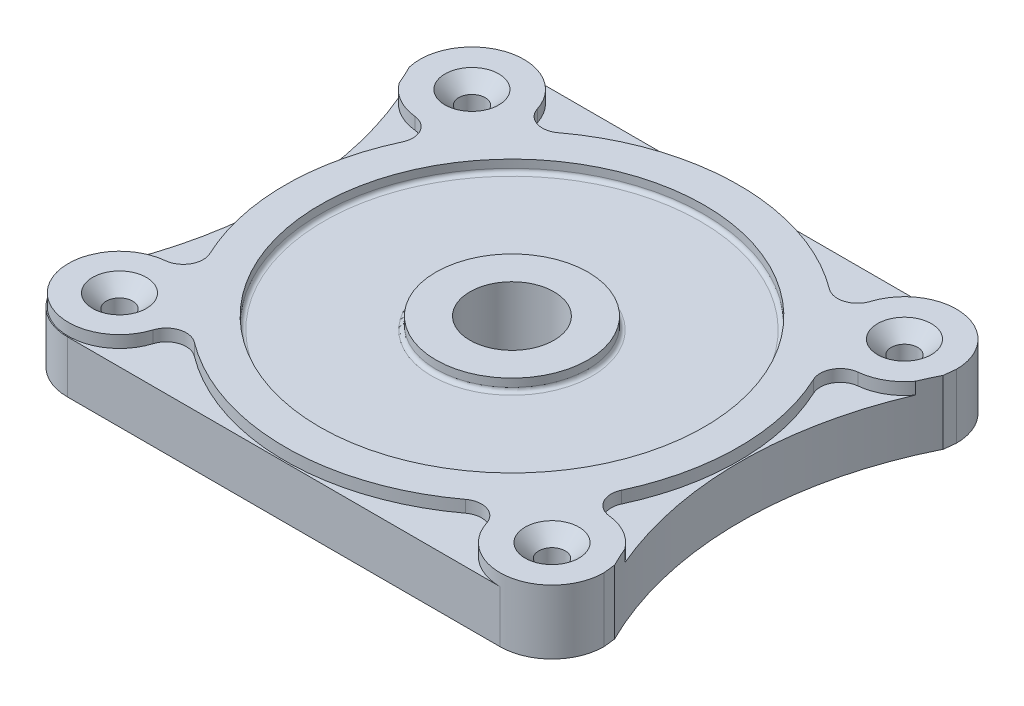
SolidWorks part; units mm, degrees
ref_plane "Front Plane" through (0, 0, 0) normal (0, 0, 1) x (1, 0, 0)
ref_plane "Top Plane" through (0, 0, 0) normal (0, 1, 0) x (1, 0, 0)
ref_plane "Right Plane" through (0, 0, 0) normal (1, 0, 0) x (0, 0, -1)
sketch "Sketch1" plane through (0, 0, 0) normal (0, 1, 0) x (1, 0, 0)
  line L1 (-67, 57) -> (67, 57)
  line L2 (-67, 57) -> (-67, -57)
  line L3 (-67, -57) -> (67, -57)
  line L4 (67, 57) -> (67, -57)
  line L5 (-67, 57) -> (67, -57) construction
  line L6 (-67, -57) -> (67, 57) construction
  point P1 (0, 0)
  dimension "D1" = 114
  dimension "D2" = 134
extrude "Boss-Extrude1" add sketch "Sketch1" along normal blind 16
sketch "Sketch2" plane through (0, 16, 0) normal (0, 1, 0) x (1, 0, 0)
  circle A0 centre (0, 0) radius 10.5
  dimension "D1" = 21
extrude "Cut-Extrude1" cut sketch "Sketch2" against normal through all
sketch "Sketch3" plane through (0, 16, 0) normal (0, 1, 0) x (1, 0, 0)
  circle A0 centre (0, 0) radius 19
  circle A1 centre (0, 0) radius 48
  dimension "D1" = 38
  dimension "D2" = 96
extrude "Cut-Extrude2" cut sketch "Sketch3" against normal blind 3
sketch "Sketch5" plane through (0, 0, 0) normal (0, -1, 0) x (1, 0, 0)
  circle A0 centre (0, 0) radius 19
  circle A1 centre (0, 0) radius 48
  dimension "D1" = 38
  dimension "D2" = 96
extrude "Cut-Extrude3" cut sketch "Sketch5" against normal blind 3
sketch "Sketch6" plane through (0, 16, 0) normal (0, 1, 0) x (1, 0, 0)
  line L0 (-220.4751, 0) -> (293.7406, 0) construction
  circle A1 centre (0, 0) radius 57 construction
  dimension "D1" = 114
hole_wizard "CSK for M6 Hex Socket Countersunk Cap Screw1" positions "Sketch7" profile "Sketch9" countersink size "M6" standard "ISO" end condition through all
sketch "Sketch7" plane through (0, 16, 0) normal (0, 1, 0) x (1, 0, 0)
  line L0 (-67, 57) -> (-67, -57) construction
  line L1 (67, -57) -> (67, 57) construction
  line L2 (-220.4751, 0) -> (293.7406, 0) construction
  point P0 (-54, 44)
  point P2 (54, 44)
  point P4 (54, -44)
  point P6 (-54, -44)
  dimension "D1" = 108
  dimension "D2" = 108
  dimension "D3" = 13
  dimension "D4" = 13
  dimension "D5" = 13
  dimension "D6" = 13
  dimension "D7" = 88
  dimension "D8" = 88
  dimension "D9" = 44
sketch "Sketch9" plane through (-54, 16, -44) normal (1, 0, 0) x (0, 0, 1)
  line L0 (0, 0) -> (0, 16)
  line L1 (0, 16) -> (3.3, 16)
  line L2 (3.3, 16) -> (3.3, 3.42)
  line L3 (3.3, 3.42) -> (6.72, 0)
  line L5 (6.72, 0) -> (0, 0)
  line L6 (-3.3, 3.42) -> (-6.72, 0) construction
  line L11 (0, -6.35) -> (0, 107.95) construction
  dimension "Thru Hole Dia." = 6.6
  dimension "Thru Hole Depth" = 16
  dimension "Near C'Sink Dia." = 13.44
  dimension "Near C'Sink Angle" = 90
sketch "Sketch10" plane through (0, 16, 0) normal (0, 1, 0) x (1, 0, 0)
  line L0 (-220.4751, 0) -> (293.7406, 0) construction
  circle A0 centre (149, 0) radius 92
  circle A1 centre (-149, 0) radius 92
  circle A2 centre (0, 0) radius 57 construction
  dimension "D1" = 184
  dimension "D2" = 184
extrude "Cut-Extrude4" cut sketch "Sketch10" against normal through all
sketch "Sketch12" plane through (0, 16, 0) normal (0, 1, 0) x (1, 0, 0)
  line L0 (-67, -41.7133) -> (-67, -57)
  line L1 (-67, -57) -> (-54, -57)
  line L2 (67, -41.7133) -> (67, -57)
  line L3 (67, -57) -> (54, -57)
  line L4 (-67, 41.7133) -> (-67, 57)
  line L5 (-67, 57) -> (-54, 57)
  line L6 (54, 57) -> (67, 57)
  line L7 (67, 57) -> (67, 41.7133)
  arc A0 (-54, 57) -> (-67, 44) centre (-54, 44) ccw
  arc A1 (67, 44) -> (54, 57) centre (54, 44) ccw
  arc A2 (-67, -44) -> (-54, -57) centre (-54, -44) ccw
  arc A3 (54, -57) -> (67, -44) centre (54, -44) ccw
  line M4 (67, 57) -> (-67, 57)
  line M5 (-67, 57) -> (-67, 41.7133)
  line M8 (-67, -57) -> (67, -57)
  line M9 (67, -57) -> (67, -41.7133)
  dimension "D1" = 26
  dimension "D2" = 26
  dimension "D3" = 26
  dimension "D4" = 26
extrude "Cut-Extrude5" cut sketch "Sketch12" against normal through all contours A2 L0 M8 | A3 M8 M9 | A0 M4 M5 | A1 L7 M4
sketch "Sketch13" plane through (0, 16, 0) normal (0, 1, 0) x (1, 0, 0)
  arc A0 (-51.3311, 23.9802) -> (-51.2311, -24.1932) centre (0, 0) ccw
  arc A1 (-55.2589, -31.3039) -> (-41.8199, -47.7973) centre (-54, -44) ccw
  arc A2 (41.6077, -47.9281) -> (55.3442, -31.0697) centre (54, -44) ccw
  arc A3 (-41.6077, 47.9281) -> (-55.3442, 31.0697) centre (-54, 44) ccw
  arc A4 (55.3442, 31.0697) -> (41.6077, 47.9281) centre (54, 44) ccw
  arc A5 (-51.3311, 23.9802) -> (-55.3442, 31.0697) centre (-55.8612, 26.0965) ccw
  arc A6 (-41.6077, 47.9281) -> (-33.8538, 45.4297) centre (-36.8414, 49.439) ccw
  arc A7 (33.8538, 45.4297) -> (41.6077, 47.9281) centre (36.8414, 49.439) ccw
  arc A8 (55.3442, 31.0697) -> (51.3311, 23.9802) centre (55.8612, 26.0965) ccw
  arc A9 (33.8538, 45.4297) -> (-33.8538, 45.4297) centre (0, 0) ccw
  arc A10 (51.3311, -23.9802) -> (55.3442, -31.0697) centre (55.8612, -26.0965) ccw
  arc A11 (-55.2589, -31.3039) -> (-51.2311, -24.1932) centre (-55.7523, -26.3283) ccw
  arc A12 (-34.0422, -45.2887) -> (-41.8199, -47.7973) centre (-37.0465, -49.2855) ccw
  arc A13 (41.6077, -47.9281) -> (33.8538, -45.4297) centre (36.8414, -49.439) ccw
  arc A14 (-34.0422, -45.2887) -> (33.8538, -45.4297) centre (0, 0) ccw
  arc A15 (51.3311, -23.9802) -> (51.3311, 23.9802) centre (0, 0) ccw
  dimension "D1" = 26
  dimension "D2" = 26
  dimension "D3" = 26
  dimension "D4" = 10
  dimension "D5" = 10
  dimension "D6" = 10
  dimension "D7" = 10
  dimension "D8" = 10
  dimension "D9" = 10
  dimension "D10" = 10
  dimension "D11" = 10
extrude "Cut-Extrude6" cut sketch "Sketch13" against normal blind 3 flip side to cut
sketch "Sketch14" plane through (0, 16, 0) normal (0, 1, 0) x (1, 0, 0)
  line L0 (67, 44) -> (66.6564, 41.0308)
  line L1 (66.6564, 41.0308) -> (67, 41.7133)
  line L2 (67, 41.7133) -> (67, 44)
  arc A0 (67, 41.7133) -> (66.6564, 41.0308) centre (149, 0) ccw construction
extrude "Cut-Extrude7" cut sketch "Sketch14" against normal through all
sketch "Sketch15" plane through (0, 13, 0) normal (0, 1, 0) x (1, 0, 0)
  line L0 (67, -41.7133) -> (66.6564, -41.0308)
  line L1 (67, -44) -> (67, -41.7133)
  line L2 (66.6564, -41.0308) -> (67, -44)
  arc A0 (41.6077, -47.9281) -> (66.6564, -41.0308) centre (54, -44) ccw construction
  arc A1 (67, -44) -> (66.6564, -41.0308) centre (54, -44) ccw construction
extrude "Cut-Extrude9" cut sketch "Sketch15" against normal through all
sketch "Sketch16" plane through (0, 16, 0) normal (0, 1, 0) x (1, 0, 0)
  line L0 (66.6564, -41.0308) -> (67, -44)
  line L1 (67, -44) -> (67.1125, -42.3347)
  line L2 (67.1125, -42.3347) -> (66.6564, -41.0308)
  arc A0 (41.6077, -47.9281) -> (66.6564, -41.0308) centre (54, -44) ccw construction
extrude "Cut-Extrude10" cut sketch "Sketch16" against normal through all
fillet "Fillet13" radius 1 1 edges at (0, 13, 19)
fillet "Fillet14" radius 1 1 edges at (0, 13, 48)
fillet "Fillet16" radius 1 1 edges at (0, 3, -19)
fillet "Fillet18" radius 1 1 edges at (0, 3, -48)
